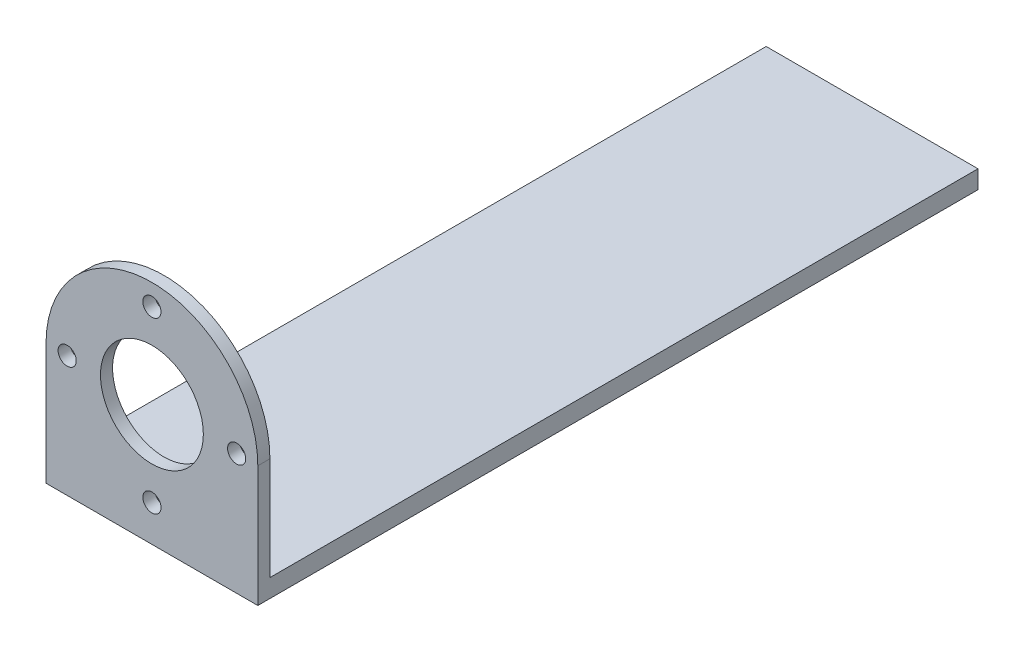
SolidWorks part; units mm, degrees
ref_plane "Front Plane" through (0, 0, 0) normal (0, 0, 1) x (1, 0, 0)
ref_plane "Top Plane" through (0, 0, 0) normal (0, 1, 0) x (1, 0, 0)
ref_plane "Right Plane" through (0, 0, 0) normal (1, 0, 0) x (0, 0, -1)
sketch "Sketch1" plane through (0, 0, 0) normal (0, 0, 1) x (1, 0, 0)
  line L0 (-17.5, 0) -> (-17.5, -20)
  line L1 (-17.5, -20) -> (17.5, -20)
  line L2 (17.5, -20) -> (17.5, 0)
  arc A0 (17.5, 0) -> (-17.5, 0) centre (0, 0) ccw
  circle A1 centre (0, 0) radius 14 construction
  circle A2 centre (0, 14) radius 1.5
  circle A4 centre (14, 0) radius 1.5
  circle A5 centre (0, -14) radius 1.5
  circle A6 centre (-14, 0) radius 1.5
  circle A7 centre (0, 0) radius 8.5
  point P18 (0, 0)
  dimension "D1" = 35
  dimension "D4" = 28
  dimension "D5" = 3
  dimension "D6" = 17
  dimension "D3" = 20
  dimension "D2" = 4
extrude "Boss-Extrude1" add sketch "Sketch1" along normal blind 2
sketch "Sketch2" plane through (0, 0, 0) normal (0, 0, -1) x (-1, 0, 0)
  line L0 (17.5, -20) -> (-17.5, -20)
  line L1 (-17.5, -20) -> (-17.5, -17)
  line L2 (-17.5, -20) -> (-17.5, 0) construction
  line L3 (-17.5, -17) -> (17.5, -17)
  line L4 (17.5, 0) -> (17.5, -20) construction
  line L5 (17.5, -17) -> (17.5, -20)
  dimension "D1" = 3
extrude "Boss-Extrude2" add sketch "Sketch2" along normal up to surface (117 mm away)
